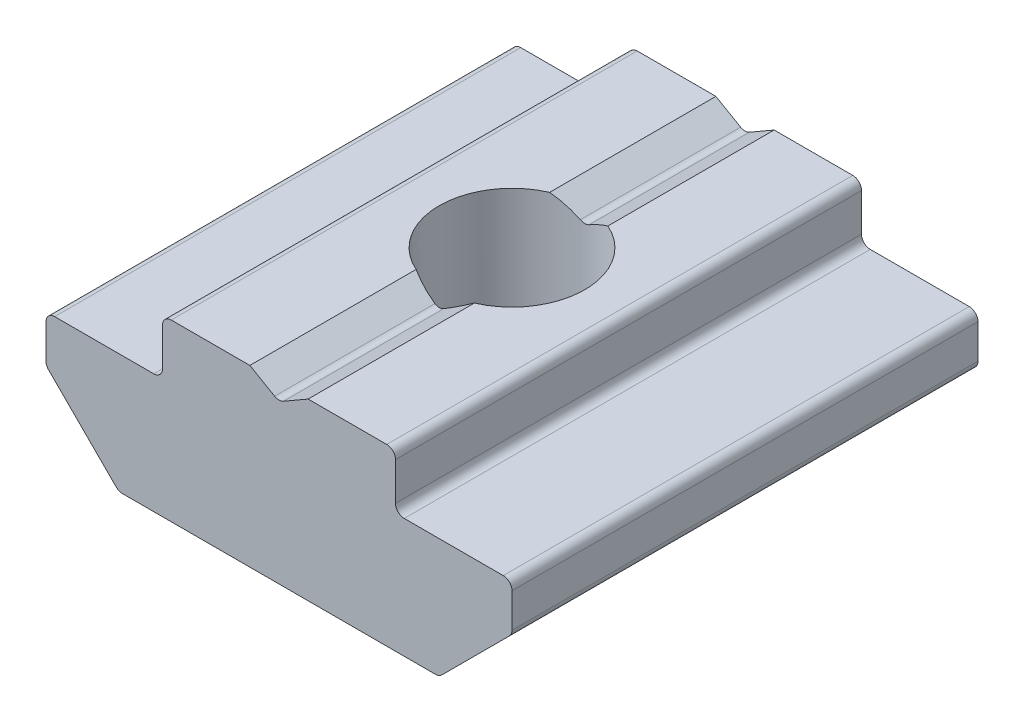
SolidWorks part; units mm, degrees
material "Chrome Stainless Steel"
ref_plane "Front Plane" through (0, 0, 0) normal (0, 0, 1) x (1, 0, 0)
ref_plane "Top Plane" through (0, 0, 0) normal (0, 1, 0) x (1, 0, 0)
ref_plane "Right Plane" through (0, 0, 0) normal (1, 0, 0) x (0, 0, -1)
sketch "Sketch1" plane through (0, 0, 0) normal (0, 0, 1) x (1, 0, 0)
  line L4 (-0.15, -0.4907) -> (-1, 0)
  line L5 (-2.46, -6) -> (2.46, -6)
  line L6 (-1, 0) -> (-0.15, -0.4907)
  line L7 (1, 0) -> (0.15, -0.4907)
  line L8 (-1, 0) -> (-3.7, 0)
  line L9 (-3.7, 0) -> (-1, 0)
  line L10 (-1, 0) -> (-0.15, -0.4907)
  line L11 (0.15, -0.4907) -> (1, 0)
  line L12 (-0.15, -0.4907) -> (-1, 0)
  line L13 (-8, -3.3757) -> (-8, -2.2)
  line L14 (5.3757, -6) -> (-5.3757, -6)
  line L15 (0.15, -0.4907) -> (1, 0)
  line L16 (1, 0) -> (0.15, -0.4907)
  line L17 (-4, -0.3) -> (-4, -1.6)
  line L18 (-4, -1.6) -> (-4, -0.3)
  line L19 (1, 0) -> (3.7, 0)
  line L20 (3.7, 0) -> (1, 0)
  line L21 (-7.7, -1.9) -> (-4.3, -1.9)
  line L22 (-8, -2.2) -> (-8, -3.3757)
  line L23 (-7.9121, -3.5879) -> (-5.5879, -5.9121)
  line L24 (-5.3757, -6) -> (5.3757, -6)
  line L25 (-5.5879, -5.9121) -> (-7.9121, -3.5879)
  line L26 (-4.3, -1.9) -> (-7.7, -1.9)
  line L27 (7.9121, -3.5879) -> (5.5879, -5.9121)
  line L28 (4, -0.3) -> (4, -1.6)
  line L29 (4, -1.6) -> (4, -0.3)
  line L30 (5.5879, -5.9121) -> (7.9121, -3.5879)
  line L31 (8, -2.2) -> (8, -3.3757)
  line L32 (4.3, -1.9) -> (7.7, -1.9)
  line L33 (7.7, -1.9) -> (4.3, -1.9)
  line L34 (8, -3.3757) -> (8, -2.2)
  ellipse E0 centre (0, -0.2309) end of major axis (0.2598, -0.0809) minor radius 0.3 (-0.15, -0.4907) -> (0.15, -0.4907) ccw
  ellipse E1 centre (0, -0.2309) end of major axis (-0.2598, -0.3809) minor radius 0.3 (-0.15, -0.4907) -> (0.15, -0.4907) ccw
  ellipse E2 centre (-3.7, -0.3) end of major axis (-4, -0.3) minor radius 0.3 (-3.7, 0) -> (-4, -0.3) ccw
  ellipse E3 centre (-3.7, -0.3) end of major axis (-3.4, -0.3) minor radius 0.3 (-3.7, 0) -> (-4, -0.3) ccw
  ellipse E4 centre (-7.7, -2.2) end of major axis (-7.4, -2.2) minor radius 0.3 (-7.7, -1.9) -> (-8, -2.2) ccw
  ellipse E5 centre (-7.7, -3.3757) end of major axis (-8, -3.3757) minor radius 0.3 (-8, -3.3757) -> (-7.9121, -3.5879) ccw
  ellipse E6 centre (-7.7, -3.3757) end of major axis (-7.7, -3.0757) minor radius 0.3 (-8, -3.3757) -> (-7.9121, -3.5879) ccw
  ellipse E7 centre (-4.3, -1.6) end of major axis (-4.3, -1.9) minor radius 0.3 (-4.3, -1.9) -> (-4, -1.6) ccw
  ellipse E8 centre (-4.3, -1.6) end of major axis (-4.3, -1.3) minor radius 0.3 (-4.3, -1.9) -> (-4, -1.6) ccw
  ellipse E9 centre (5.3757, -5.7) end of major axis (5.0757, -5.7) minor radius 0.3 (5.3757, -6) -> (5.5879, -5.9121) ccw
  ellipse E10 centre (-5.3757, -5.7) end of major axis (-5.5879, -5.4879) minor radius 0.3 (-5.5879, -5.9121) -> (-5.3757, -6) ccw
  ellipse E11 centre (-7.7, -2.2) end of major axis (-8, -2.2) minor radius 0.3 (-7.7, -1.9) -> (-8, -2.2) ccw
  ellipse E12 centre (-5.3757, -5.7) end of major axis (-5.1636, -5.9121) minor radius 0.3 (-5.5879, -5.9121) -> (-5.3757, -6) ccw
  ellipse E13 centre (5.3757, -5.7) end of major axis (5.6757, -5.7) minor radius 0.3 (5.3757, -6) -> (5.5879, -5.9121) ccw
  ellipse E14 centre (3.7, -0.3) end of major axis (4, -0.3) minor radius 0.3 (4, -0.3) -> (3.7, 0) ccw
  ellipse E15 centre (3.7, -0.3) end of major axis (4, -0.3) minor radius 0.3 (4, -0.3) -> (3.7, 0) ccw
  ellipse E16 centre (7.7, -3.3757) end of major axis (7.4879, -3.5879) minor radius 0.3 (7.9121, -3.5879) -> (8, -3.3757) ccw
  ellipse E17 centre (4.3, -1.6) end of major axis (4.6, -1.6) minor radius 0.3 (4, -1.6) -> (4.3, -1.9) ccw
  ellipse E18 centre (4.3, -1.6) end of major axis (4, -1.6) minor radius 0.3 (4, -1.6) -> (4.3, -1.9) ccw
  ellipse E19 centre (7.7, -3.3757) end of major axis (7.9121, -3.1636) minor radius 0.3 (7.9121, -3.5879) -> (8, -3.3757) ccw
  ellipse E20 centre (7.7, -2.2) end of major axis (7.7, -2.5) minor radius 0.3 (8, -2.2) -> (7.7, -1.9) ccw
  ellipse E21 centre (7.7, -2.2) end of major axis (8, -2.2) minor radius 0.3 (8, -2.2) -> (7.7, -1.9) ccw
  spline S0 degree 3 poles (0.15, -0.4907) (0.1387, -0.4973) (0.127, -0.5031) (0.0779, -0.5234) (0.0377, -0.5309) (-0.0377, -0.5309) (-0.0779, -0.5234) (-0.127, -0.5031) (-0.1387, -0.4973) (-0.15, -0.4907) knots 1.207364 1.207364 1.207364 1.207364 1.244397 1.244397 1.357524 1.357524 1.47065 1.47065 1.507683 1.507683 1.507683 1.507683
  spline S1 degree 3 poles (-0.15, -0.4907) (-0.1387, -0.4973) (-0.127, -0.5031) (-0.0779, -0.5234) (-0.0377, -0.5309) (0.0377, -0.5309) (0.0779, -0.5234) (0.127, -0.5031) (0.1387, -0.4973) (0.15, -0.4907) knots 0.302348 0.302348 0.302348 0.302348 0.339381 0.339381 0.452508 0.452508 0.565634 0.565634 0.602667 0.602667 0.602667 0.602667
extrude "Extrude1" add sketch "Sketch1" along normal blind 16 contours L31 E20 L32 E17 L28 E14 L19 L7 E1 E0 L4 L8 E2 L17 E7 L21 E4 L13 E5 L23 E10 L14 L5 E9 L27 E16
sketch "Sketch2" plane through (0, 0, 0) normal (0, 1, 0) x (1, 0, 0)
  circle A0 centre (0, -8) radius 2.5
  dimension "D1" = 5
extrude "Cut-Extrude1" cut sketch "Sketch2" against normal through all
